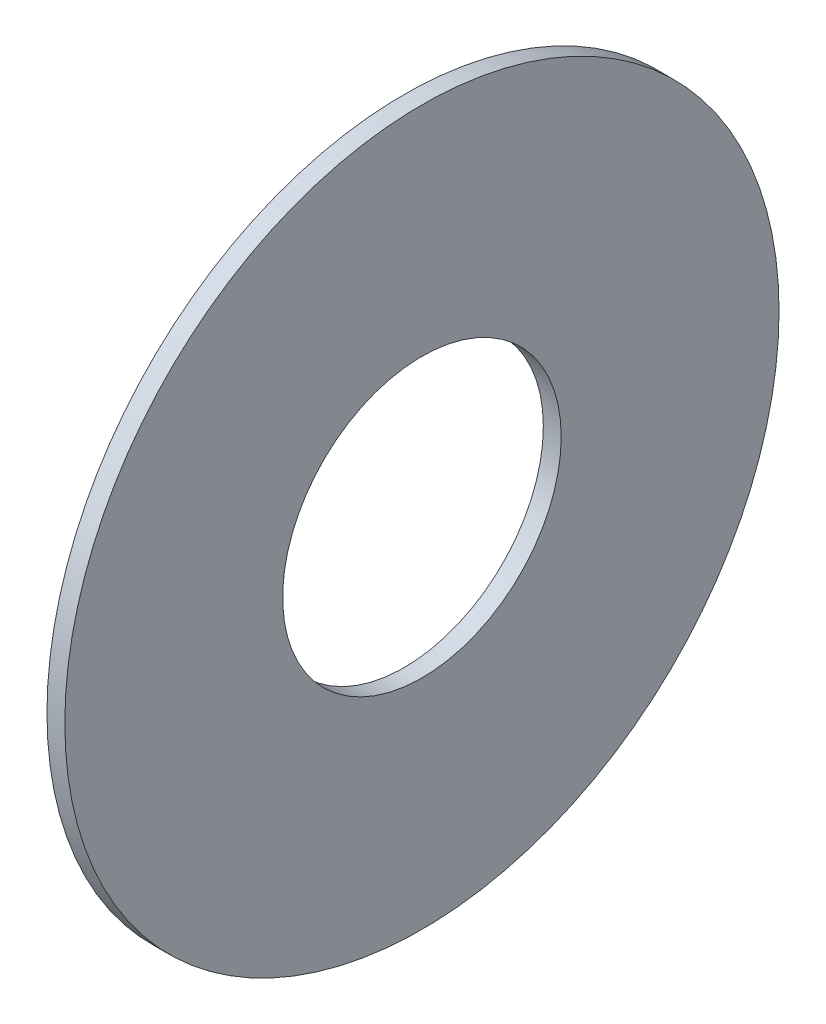
SolidWorks part; units mm, degrees
material "Silicon Rubber"
ref_plane "Front Plane" through (0, 0, 0) normal (0, 0, 1) x (1, 0, 0)
ref_plane "Top Plane" through (0, 0, 0) normal (0, 1, 0) x (1, 0, 0)
ref_plane "Right Plane" through (0, 0, 0) normal (1, 0, 0) x (0, 0, -1)
sketch "Sketch1" plane through (0, 0, 0) normal (1, 0, 0) x (0, 0, -1)
  circle A0 centre (0, 0) radius 63.5
  circle A1 centre (0, 0) radius 24.765
  dimension "D1" = 127
  dimension "D2" = 49.53
extrude "Boss-Extrude1" add sketch "Sketch1" along normal blind 3.175
